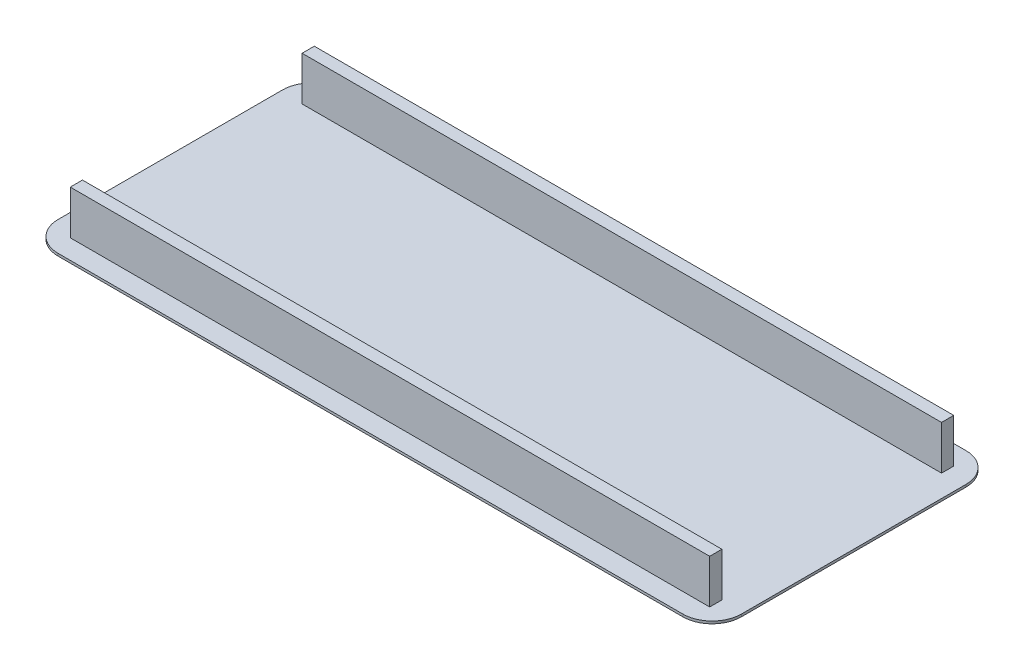
SolidWorks part; units mm, degrees
ref_plane "前视基准面" through (0, 0, 0) normal (0, 0, 1) x (1, 0, 0)
ref_plane "上视基准面" through (0, 0, 0) normal (0, 1, 0) x (1, 0, 0)
ref_plane "右视基准面" through (0, 0, 0) normal (1, 0, 0) x (0, 0, -1)
sketch "草图1" plane through (0, 0, 0) normal (0, 1, 0) x (1, 0, 0)
  line L1 (-64, 29) -> (64, 29)
  line L2 (-70, 23) -> (-70, -23)
  line L3 (-64, -29) -> (64, -29)
  line L4 (70, 23) -> (70, -23)
  line L5 (-70, 29) -> (70, -29) construction
  line L6 (-70, -29) -> (70, 29) construction
  arc A0 (64, 29) -> (70, 23) centre (64, 23) cw
  arc A1 (70, -23) -> (64, -29) centre (64, -23) cw
  arc A2 (-70, -23) -> (-64, -29) centre (-64, -23) ccw
  arc A3 (-70, 23) -> (-64, 29) centre (-64, 23) cw
  point P0 (0, 0)
  dimension "D3" = 6
  dimension "D1" = 140
  dimension "D2" = 58
extrude "凸台-拉伸1" add sketch "草图1" along normal blind 0.5
sketch "草图2" plane through (0, 0.5, 0) normal (0, 1, 0) x (1, 0, 0)
  line L0 (0, 0) -> (-64.531, 0) construction
  line L1 (0, 0) -> (0, -52.5657) construction
  line L2 (65.5, -25) -> (-65.5, -25)
  line L3 (-65.5, -25) -> (-65.5, -22.5)
  line L4 (-65.5, -22.5) -> (65.5, -22.5)
  line L5 (65.5, -25) -> (65.5, -22.5)
  line L6 (-65.5, 25) -> (-65.5, 22.5)
  line L7 (65.5, 25) -> (-65.5, 25)
  line L8 (65.5, 25) -> (65.5, 22.5)
  line L9 (-65.5, 22.5) -> (65.5, 22.5)
  point P4 (0, -25)
  point P12 (0, -22.5)
  dimension "D1" = 65.5
  dimension "D2" = 2.5
  dimension "D3" = 22.5
extrude "凸台-拉伸2" add sketch "草图2" along normal blind 9
sketch "草图3" plane through (0, 0, 0) normal (0, -1, 0) x (1, 0, 0)
  text T0 "Smart Clock" font "SWMono" height 3.5
extrude "切除-拉伸2" cut sketch "草图3" against normal blind 0.3
